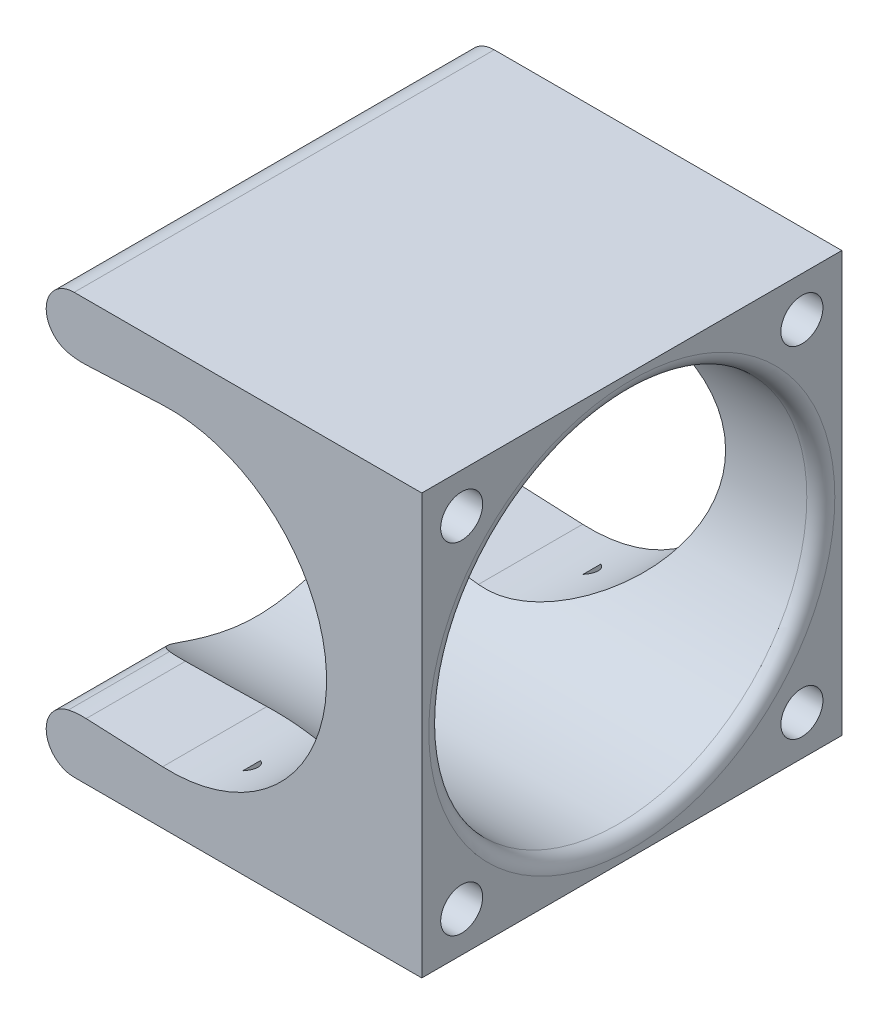
SolidWorks part; units mm, degrees
ref_plane "前视基准面" through (0, 0, 0) normal (0, 0, 1) x (1, 0, 0)
ref_plane "上视基准面" through (0, 0, 0) normal (0, 1, 0) x (1, 0, 0)
ref_plane "右视基准面" through (0, 0, 0) normal (1, 0, 0) x (0, 0, -1)
sketch "草图1" plane through (0, 0, 0) normal (0, 0, 1) x (1, 0, 0)
  line B0 (18, -15) -> (-6.8275, -15)
  line B1 (18, 15) -> (-6.8275, 15)
  line B2 (18, 15) -> (18, -15)
  line B3 (-5.9718, 10.9389) -> (-0.5111, 11.1883)
  line B4 (-5.9718, -10.9389) -> (-0.5111, -11.1883)
  arc B5 (-0.5111, -11.1883) -> (-0.5111, 11.1883) centre (0, 0) ccw
  arc B6 (-7.2458, 11.0442) -> (-5.9718, 10.9389) centre (-6.2, 15.9336) ccw
  arc B7 (-5.9718, -10.9389) -> (-7.2458, -11.0442) centre (-6.2, -15.9336) ccw
  arc B8 (-7.2458, -11.0442) -> (-6.8275, -15) centre (-6.8275, -13) ccw
  arc B9 (-6.8275, 15) -> (-7.2458, 11.0442) centre (-6.8275, 13) ccw
sketch_block_instance "块1-1"
sketch_block "块1"
extrude "凸台-拉伸1" add sketch "草图1" along normal blind 30
sketch "草图2" plane through (18, 0, 0) normal (1, 0, 0) x (0, 0, -1)
  line L0 (-30, 15) -> (0, 15) construction
  line L1 (0, -15) -> (0, 15) construction
  circle A0 centre (-15, 0) radius 13.5
  dimension "D1" = 27
  dimension "D2" = 15
  dimension "D3" = 15
extrude "切除-拉伸1" cut sketch "草图2" against normal through all
sketch "草图3" plane through (18, 0, 0) normal (1, 0, 0) x (0, 0, -1)
  line L0 (-30, -15) -> (-30, 15) construction
  line L1 (-30, 15) -> (0, 15) construction
  line L2 (0, -15) -> (0, 15) construction
  line L3 (-30, -15) -> (0, -15) construction
  circle A0 centre (-27.15, 12.15) radius 1.5
  circle A1 centre (-2.85, 12.15) radius 1.5
  circle A2 centre (-2.85, -12.15) radius 1.5
  circle A3 centre (-27.15, -12.15) radius 1.5
  dimension "D5" = 3
  dimension "D1" = 2.85
  dimension "D2" = 2.85
  dimension "D3" = 2.85
  dimension "D4" = 2.85
extrude "切除-拉伸2" cut sketch "草图3" against normal blind 15
fillet "圆角1" radius 1 1 edges at (18, 0, 1.5)
